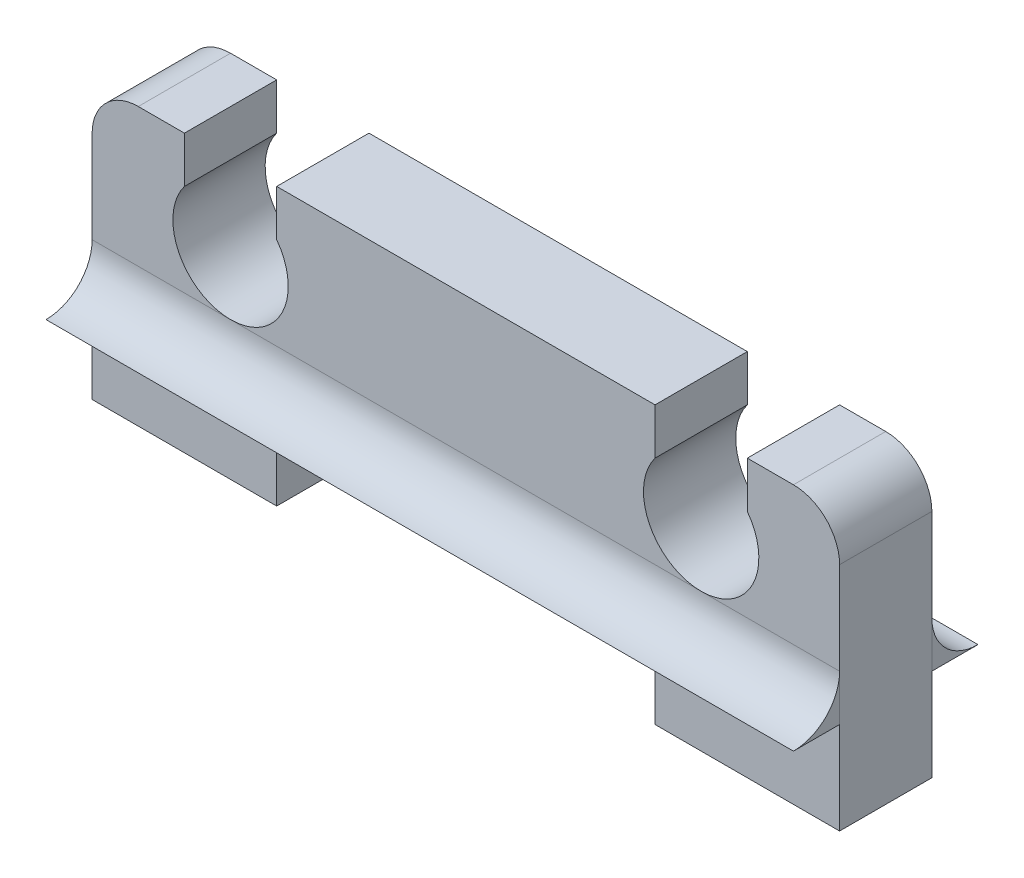
SolidWorks part; units mm, degrees
ref_plane "Front Plane" through (0, 0, 0) normal (0, 0, 1) x (1, 0, 0)
ref_plane "Top Plane" through (0, 0, 0) normal (0, 1, 0) x (1, 0, 0)
ref_plane "Right Plane" through (0, 0, 0) normal (1, 0, 0) x (0, 0, -1)
sketch "Sketch1" plane through (0, 0, 0) normal (0, 0, 1) x (1, 0, 0)
  line L0 (4, 8) -> (12.2, 8)
  line L1 (4, 4) -> (12.2, 4)
  line L2 (16.2, 0) -> (16.2, 7)
  line L3 (0, 0) -> (4, 0)
  line L4 (4, 0) -> (4, 4)
  line L5 (2, 8) -> (2, 7)
  line L6 (12.2, 8) -> (12.2, 7)
  line L7 (2, 8) -> (1, 8)
  line L8 (4, 8) -> (4, 7)
  line L9 (14.2, 8) -> (15.2, 8)
  line L10 (14.2, 8) -> (14.2, 7)
  line L11 (12.2, 0) -> (12.2, 4)
  line L12 (0, 0) -> (0, 7)
  line L13 (16.2, 0) -> (12.2, 0)
  line L14 (8.1, 4) -> (8.1, 8) construction
  arc A0 (15.2, 8) -> (16.2, 7) centre (15.2, 7) cw
  arc A1 (2, 7) -> (4, 7) centre (3, 6.25) ccw
  arc A2 (14.2, 7) -> (12.2, 7) centre (13.2, 6.25) cw
  arc A3 (1, 8) -> (0, 7) centre (1, 7) ccw
  dimension "D1" = 1.25
  dimension "D2" = 1
  dimension "D3" = 3
  dimension "D4" = 4
  dimension "D5" = 8.1
extrude "Boss-Extrude1" add sketch "Sketch1" along normal blind 2
sketch "Sketch2" plane through (0, 0, 0) normal (-1, 0, 0) x (0, 0, 1)
  line L0 (1, 0) -> (1, 7) construction
  line L1 (2, 7) -> (2, 0) construction
  line L2 (2, 4) -> (2, 5)
  line L3 (2, 4) -> (3, 4)
  line L4 (2, 0) -> (0, 0) construction
  line L5 (2, 7) -> (0, 7) construction
  line L6 (0, 4) -> (-1, 4)
  line L7 (0, 4) -> (0, 5)
  arc A0 (2, 5) -> (3, 4) centre (3, 5) ccw
  arc A1 (0, 5) -> (-1, 4) centre (-1, 5) cw
  dimension "D2" = 1
  dimension "D1" = 4
extrude "Boss-Extrude2" add sketch "Sketch2" against normal blind 16.2 separate body
sketch "Sketch3" plane through (0, 0, 2) normal (0, 0, 1) x (1, 0, 0)
  line L0 (0, 0) -> (0, 2)
  line L1 (0, 7) -> (0, 0) construction
  line L2 (0, 2) -> (4, 2)
  line L3 (4, 0) -> (4, 4) construction
  line L4 (4, 2) -> (4, 0)
  line L5 (4, 0) -> (0, 0)
  line L6 (8.1, 8) -> (8.1, 0) construction
  line L7 (12.2, 8) -> (4, 8) construction
  line L8 (12.2, 0) -> (16.2, 0)
  line L9 (12.2, 2) -> (12.2, 0)
  line L10 (16.2, 2) -> (12.2, 2)
  line L11 (16.2, 0) -> (16.2, 2)
extrude "Cut-Extrude1" cut sketch "Sketch3" against normal through all
equation "\"D5@Sketch1\"= \"fingerWidth@parametersSketch@prostheticParameters.SLDPRT\" / 2"
equation "\"D1@Boss-Extrude2\"= \"fingerWidth@parametersSketch@prostheticParameters.SLDPRT\"'Radius of Tube Driver"
